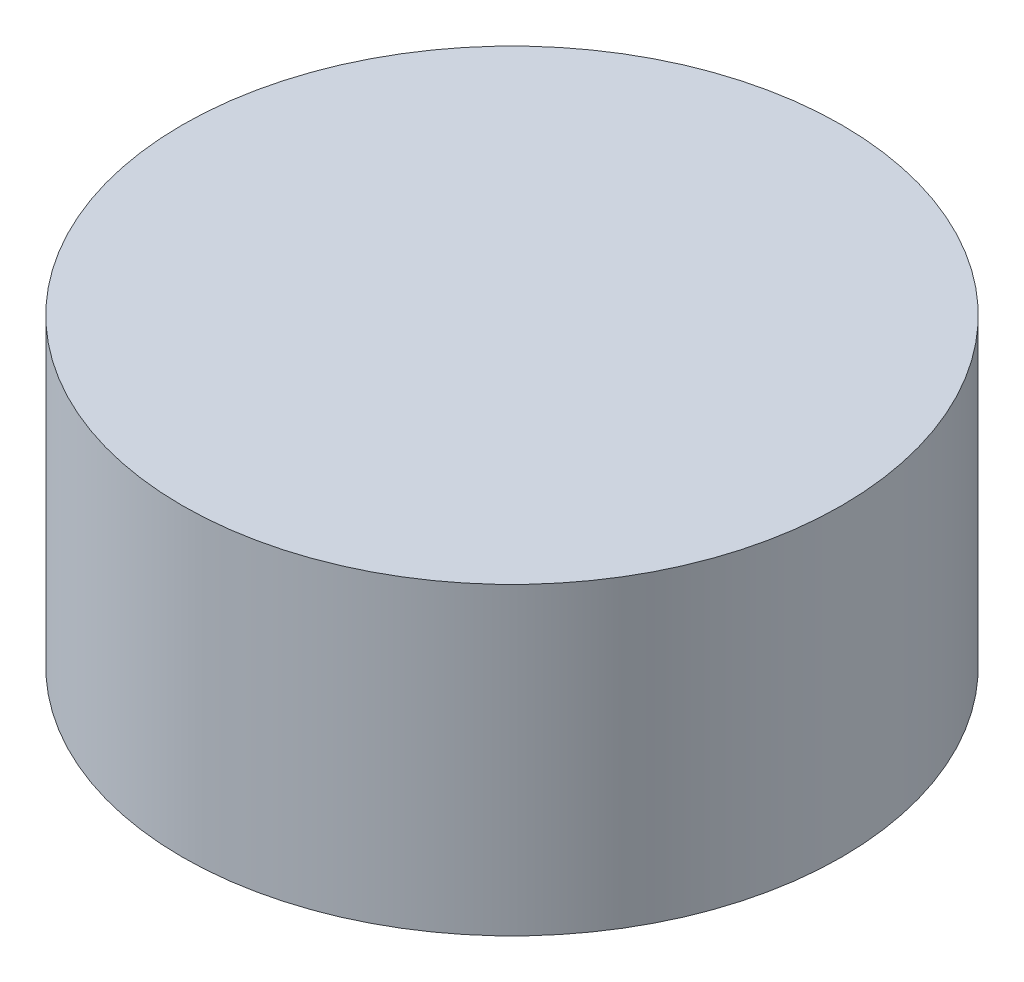
SolidWorks part; units mm, degrees
ref_plane "前基準面" through (0, 0, 0) normal (0, 0, 1) x (1, 0, 0)
ref_plane "上基準面" through (0, 0, 0) normal (0, 1, 0) x (1, 0, 0)
ref_plane "右基準面" through (0, 0, 0) normal (1, 0, 0) x (0, 0, -1)
sketch "草圖1" plane through (0, 0, 0) normal (0, 1, 0) x (1, 0, 0)
  line L5 (57.3142, 17.0177) -> (109.2654, 17.0177)
  line L6 (57.3142, 17.0177) -> (57.3142, -17.0177)
  line L7 (57.3142, -17.0177) -> (109.2654, -17.0177)
  line L8 (109.2654, 17.0177) -> (109.2654, -17.0177)
  circle A0 centre (0, 0) radius 64.982
  circle A3 centre (109.2654, 0) radius 16.1017
extrude "填料-伸長3" add sketch "草圖1" along normal blind 60 contours A0
sketch "草圖2" plane through (0, 0, 0) normal (0, -1, 0) x (1, 0, 0)
  line L0 (0, 0) -> (64.982, 0)
  circle A0 centre (0, 0) radius 64.982 construction
